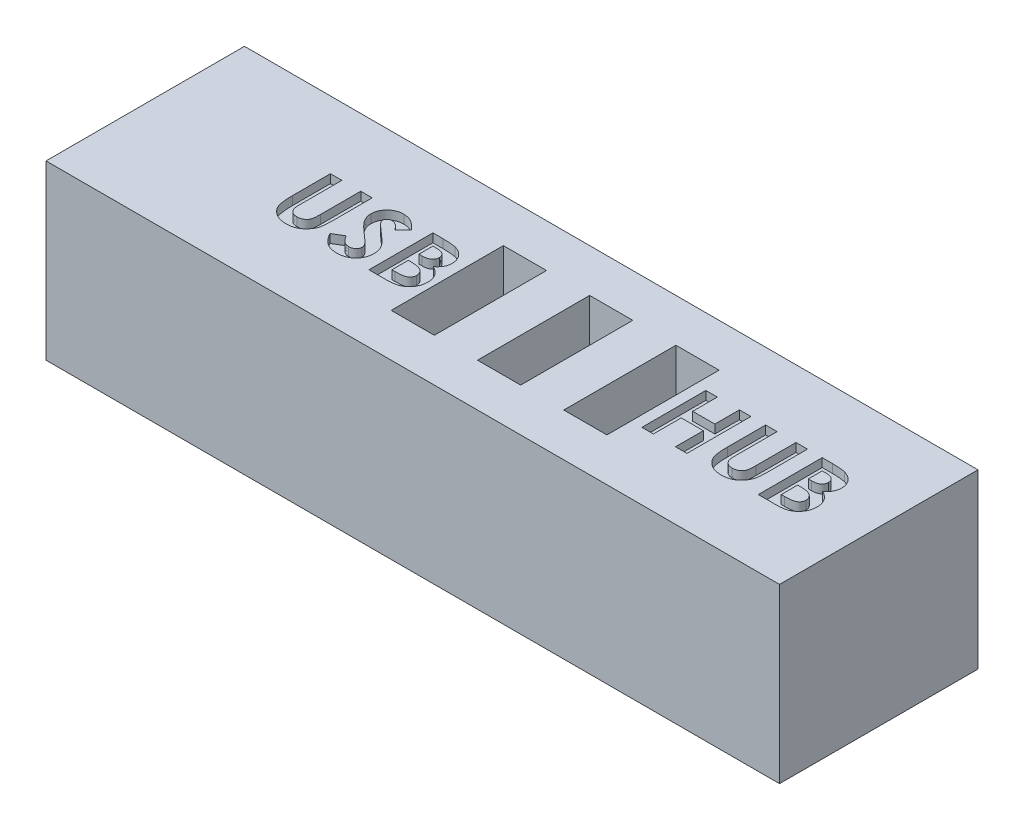
SolidWorks part; units mm, degrees
ref_plane "Front Plane" through (0, 0, 0) normal (0, 0, 1) x (1, 0, 0)
ref_plane "Top Plane" through (0, 0, 0) normal (0, 1, 0) x (1, 0, 0)
ref_plane "Right Plane" through (0, 0, 0) normal (1, 0, 0) x (0, 0, -1)
sketch "Sketch1" plane through (0, 0, 0) normal (0, 1, 0) x (1, 0, 0)
  line L1 (-42.5, -11.5) -> (42.5, -11.5)
  line L2 (-42.5, -11.5) -> (-42.5, 11.5)
  line L3 (-42.5, 11.5) -> (42.5, 11.5)
  line L4 (42.5, -11.5) -> (42.5, 11.5)
  line L5 (-42.5, -11.5) -> (42.5, 11.5) construction
  line L6 (-42.5, 11.5) -> (42.5, -11.5) construction
  point P0 (0, 0)
  dimension "D1" = 85
  dimension "D2" = 23
extrude "Boss-Extrude1" add sketch "Sketch1" along normal blind 20
sketch "Sketch2" plane through (0, 20, 0) normal (0, 1, 0) x (1, 0, 0)
  line L0 (2.5, 6.5) -> (7.5, 6.5)
  line L1 (-7.5, -6.5) -> (-2.5, -6.5)
  line L2 (-7.5, -6.5) -> (-7.5, 6.5)
  line L3 (-7.5, 6.5) -> (-2.5, 6.5)
  line L4 (-2.5, -6.5) -> (-2.5, 6.5)
  line L5 (-7.5, -6.5) -> (-2.5, 6.5) construction
  line L6 (-7.5, 6.5) -> (-2.5, -6.5) construction
  line L7 (2.5, -6.5) -> (2.5, 6.5)
  line L8 (7.5, -6.5) -> (7.5, 6.5)
  line L9 (2.5, -6.5) -> (7.5, -6.5)
  line L10 (12.5, 6.5) -> (17.5, 6.5)
  line L11 (12.5, -6.5) -> (12.5, 6.5)
  line L12 (17.5, -6.5) -> (17.5, 6.5)
  line L13 (12.5, -6.5) -> (17.5, -6.5)
  line L17 (-42.5, 11.5) -> (-42.5, -11.5) construction
  point P0 (-5, 0)
  dimension "D1" = 13
  dimension "D2" = 5
  dimension "D5" = 35
  dimension "D4" = 3
extrude "Cut-Extrude1" cut sketch "Sketch2" against normal blind 10
sketch "Sketch3" plane through (0, 20, 0) normal (0, 1, 0) x (1, 0, 0)
  text T0 "USB         HUB" font "Century Gothic" height in points 28
extrude "Cut-Extrude2" cut sketch "Sketch3" against normal blind 1
